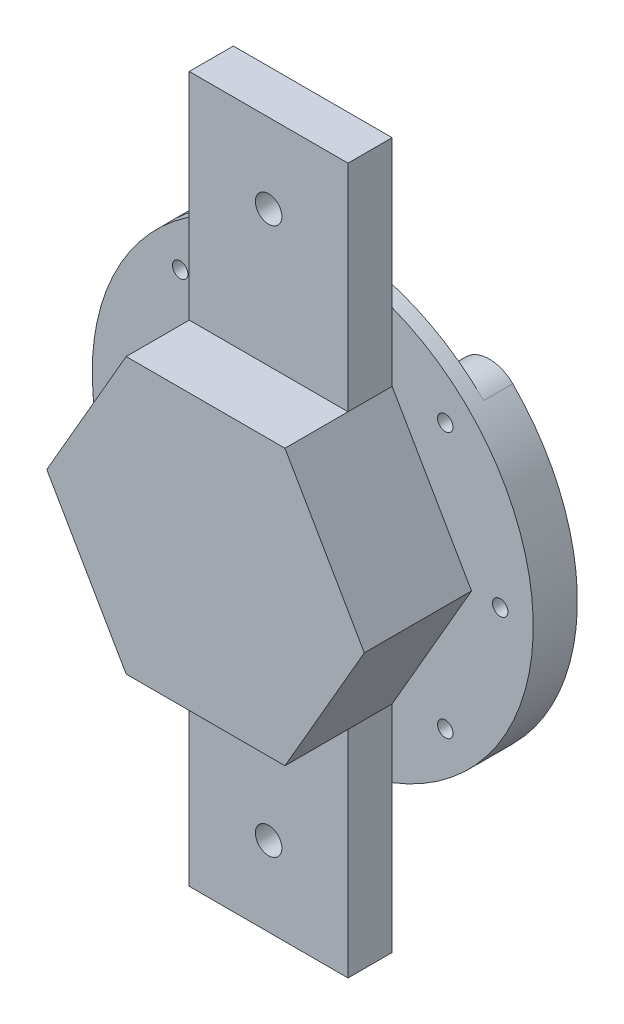
SolidWorks part; units mm, degrees
ref_plane "前视基准面" through (0, 0, 0) normal (0, 0, 1) x (1, 0, 0)
ref_plane "上视基准面" through (0, 0, 0) normal (0, 1, 0) x (1, 0, 0)
ref_plane "右视基准面" through (0, 0, 0) normal (1, 0, 0) x (0, 0, -1)
sketch "草图1" plane through (0, 0, 0) normal (0, 0, 1) x (1, 0, 0)
  line L0 (20.5061, -20.5061) -> (24.7487, -24.7487)
  line L1 (28.8675, -50) -> (57.735, 0)
  line L2 (57.735, 0) -> (28.8675, 50)
  line L3 (28.8675, 50) -> (-28.8675, 50)
  line L4 (-28.8675, 50) -> (-57.735, 0)
  line L5 (-57.735, 0) -> (-28.8675, -50)
  line L6 (-28.8675, -50) -> (28.8675, -50)
  line L7 (24.7487, 24.7487) -> (20.5061, 20.5061)
  line L8 (-24.7487, 24.7487) -> (-20.5061, 20.5061)
  line L9 (-20.5061, -20.5061) -> (-24.7487, -24.7487)
  line L10 (-24.7487, 24.7487) -> (-35.3553, 35.3553)
  line L11 (-35.3553, 35.3553) -> (-20.5061, 20.5061)
  line L12 (-20.5061, -20.5061) -> (-35.3553, -35.3553)
  line L13 (-35.3553, -35.3553) -> (-20.5061, -20.5061)
  line L14 (20.5061, 20.5061) -> (35.3553, 35.3553)
  line L15 (20.5061, -20.5061) -> (30.052, -30.052)
  line L16 (30.052, -30.052) -> (35.3553, -35.3553)
  arc A0 (-35.3553, 35.3553) -> (0, 50) centre (0, 0) ccw construction
  arc A1 (-1.7496, -42.464) -> (1.7496, -42.464) centre (0, 0) ccw
  arc A3 (-20.5061, 20.5061) -> (-20.5061, -20.5061) centre (0, 0) ccw
  circle A4 centre (-42.5, 0) radius 1.75
  circle A5 centre (-30.052, 30.052) radius 1.75
  circle A6 centre (0, 42.5) radius 1.75
  circle A7 centre (30.052, 30.052) radius 1.75
  circle A8 centre (42.5, 0) radius 1.75
  circle A9 centre (30.052, -30.052) radius 1.75
  circle A10 centre (0, -42.5) radius 1.75
  circle A11 centre (-30.052, -30.052) radius 1.75
  arc A12 (20.5061, -20.5061) -> (20.5061, 20.5061) centre (0, 0) ccw
  arc A13 (-35.3553, 35.3553) -> (35.3553, 35.3553) centre (0, 0) ccw
  arc A14 (1.7496, 42.464) -> (-1.7496, 42.464) centre (0, 0) ccw
  arc A15 (30.052, -30.052) -> (28.7894, 31.2637) centre (0, 0) ccw
  arc A16 (-28.7894, 31.2637) -> (-28.7894, -31.2637) centre (0, 0) ccw
  arc A17 (35.3553, 35.3553) -> (24.7487, 24.7487) centre (30.052, 30.052) ccw
  arc A18 (-35.3553, 35.3553) -> (-24.7487, 24.7487) centre (-30.052, 30.052) cw
  arc A19 (-24.7487, -24.7487) -> (-35.3553, -35.3553) centre (-30.052, -30.052) cw
  arc A20 (24.7487, -24.7487) -> (35.3553, -35.3553) centre (30.052, -30.052) ccw
  point P1 (0, 50)
  point P32 (0, 0)
  dimension "D1" = 100
  dimension "D2" = 8
extrude "凸台-拉伸1" add sketch "草图1" along normal blind 6.6 contours L14 A17 A7 | A15 A8 A9 L16 A13 L14 A7 | A8 A15 A7 L14 L7 A12 L0 L15 A9 | L15 A20 L16 A9 | A19 L12 A11 | A5 A16 A4 A11 L12 L9 A3 L8 L10 | A16 A5 L10 A13 L12 A11 A4 | A18 L10 A5
sketch "草图2" plane through (0, 0, 6.6) normal (0, 0, 1) x (1, 0, 0)
  circle A0 centre (0, 0) radius 50
extrude "凸台-拉伸2" add sketch "草图2" along normal blind 3.4
sketch "草图4" plane through (0, 0, 6.6) normal (0, 0, -1) x (-1, 0, 0)
  circle A0 centre (-42.5, 0) radius 1.75
  circle A1 centre (-30.052, 30.052) radius 1.75
  circle A2 centre (0, 42.5) radius 1.75
  circle A3 centre (30.052, 30.052) radius 1.75
  circle A4 centre (42.5, 0) radius 1.75
  circle A5 centre (30.052, -30.052) radius 1.75
  circle A6 centre (0, -42.5) radius 1.75
  circle A7 centre (-30.052, -30.052) radius 1.75
  point P20 (0, 0)
  dimension "D1" = 8
extrude "切除-拉伸2" cut sketch "草图4" against normal mid plane 20 contours A0 | A1 | A7 | A5 | A4 | A3
sketch "草图5" plane through (0, 0, 10) normal (0, 0, 1) x (1, 0, 0)
  line L0 (-18, -31.1769) -> (-18, -80)
  line L1 (36, 0) -> (18, 31.1769)
  line L3 (-18, 31.1769) -> (-36, 0)
  line L4 (-36, 0) -> (-18, -31.1769)
  line L6 (18, -31.1769) -> (36, 0)
  line L7 (-18, 80) -> (18, 80)
  line L8 (-18, 80) -> (-18, 31.1769)
  line L9 (-18, -80) -> (18, -80)
  line L10 (18, 80) -> (18, 31.1769)
  line L13 (18, -31.1769) -> (18, -80)
  line L16 (18, 31.1769) -> (-18, 31.1769) [skipped]
  line L17 (7.0148, -31.1769) -> (18, -31.1769) [skipped]
  dimension "D1" = 160
extrude "凸台-拉伸7" add sketch "草图5" along normal blind 20
sketch "草图10" plane through (0, 0, 30) normal (0, 0, 1) x (1, 0, 0)
  line L0 (-18, -31.1769) -> (-18, -80)
  line L1 (-18, 80) -> (18, 80)
  line L2 (-18, 80) -> (-18, 31.1769)
  line L3 (-18, -80) -> (18, -80)
  line L4 (18, 80) -> (18, 31.1769)
  line L8 (18, 31.1769) -> (-18, 31.1769)
  line L11 (-18, -31.1769) -> (18, -31.1769)
  line L15 (18, -31.1769) -> (18, -80)
  line L16 (18, -31.1769) -> (27, -15.5885) [skipped]
  line L17 (-36, 0) -> (-27, -15.5885) [skipped]
  line L18 (-18, 31.1769) -> (-27, 15.5885) [skipped]
  line L19 (27, 15.5885) -> (18, 31.1769) [skipped]
  point P0 (0, 0)
extrude "切除-拉伸3" cut sketch "草图10" against normal blind 10
sketch "草图11" plane through (0, 0, 20) normal (0, 0, 1) x (1, 0, 0)
  line L0 (18, 80) -> (-18, 80) construction
  circle A0 centre (0, 62) radius 3
  dimension "D2" = 6
  dimension "D1" = 18
extrude "切除-拉伸6" cut sketch "草图11" against normal blind 10 contours A0
mirror "镜向2" about plane through (0, 0, 0) normal (0, 1, 0) of "切除-拉伸6"
sketch "草图12" plane through (0, 0, 30) normal (0, 0, 1) x (1, 0, 0)
  line L1 (36, 0) -> (18, 31.1769)
  line L2 (18, 31.1769) -> (-18, 31.1769)
  line L3 (-18, 31.1769) -> (-36, 0)
  line L4 (-36, 0) -> (-18, -31.1769)
  line L5 (-18, -31.1769) -> (18, -31.1769)
  line L6 (18, -31.1769) -> (36, 0)
  circle A0 centre (0, 0) radius 36 construction
extrude "凸台-拉伸8" add sketch "草图12" along normal blind 4.3
